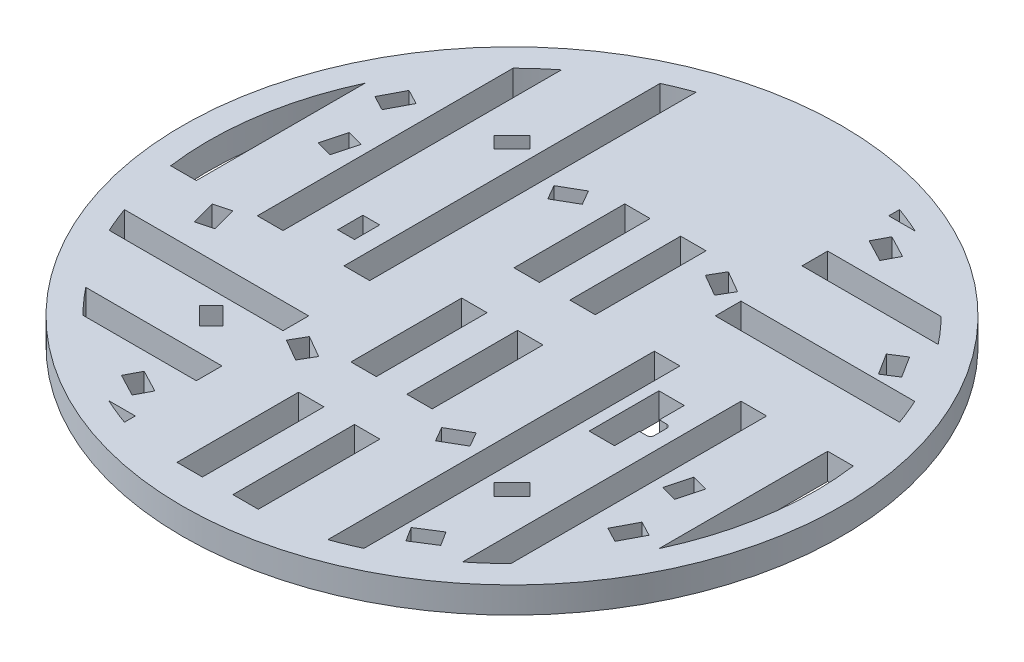
SolidWorks part; units mm, degrees
material "Acrylic (Medium-high impact)"
ref_plane "Front Plane" through (0, 0, 0) normal (0, 0, 1) x (1, 0, 0)
ref_plane "Top Plane" through (0, 0, 0) normal (0, 1, 0) x (1, 0, 0)
ref_plane "Right Plane" through (0, 0, 0) normal (1, 0, 0) x (0, 0, -1)
sketch "스케치1" plane through (0, 0, 0) normal (0, 1, 0) x (1, 0, 0)
  line L0 (-4.66, 33.75) -> (-4.66, -33.75) construction
  line L1 (-17, -33.75) -> (17, -33.75) construction
  line L2 (-17, -33.75) -> (-17, 33.75)
  line L3 (-17, 33.75) -> (17, 33.75) construction
  line L4 (17, -33.75) -> (17, 33.75)
  line L5 (-17, -33.75) -> (17, 33.75) construction
  line L6 (-17, 33.75) -> (17, -33.75) construction
  line L7 (-4.66, 4.89) -> (-1.75, 4.89)
  line L8 (-4.66, 4.89) -> (-4.66, 17.59)
  line L9 (-4.66, 17.59) -> (-1.75, 17.59)
  line L10 (-1.75, 4.89) -> (-1.75, 17.59)
  line L11 (-4.66, 4.89) -> (-1.75, 17.59) construction
  line L12 (-4.66, 17.59) -> (-1.75, 4.89) construction
  line L13 (-4.66, -13.81) -> (-1.75, -13.81)
  line L14 (-4.66, -13.81) -> (-4.66, -1.11)
  line L15 (-4.66, -1.11) -> (-1.75, -1.11)
  line L16 (-1.75, -13.81) -> (-1.75, -1.11)
  line L17 (-4.66, -13.81) -> (-1.75, -1.11) construction
  line L18 (-4.66, -1.11) -> (-1.75, -13.81) construction
  line L19 (-4.66, 23.59) -> (-1.75, 23.59) construction
  line L20 (-4.66, 23.59) -> (-4.66, 33.75) construction
  line L21 (-4.66, 33.75) -> (-1.75, 33.75) construction
  line L22 (-1.75, 23.59) -> (-1.75, 33.75) construction
  line L23 (-4.66, 23.59) -> (-1.75, 33.75) construction
  line L24 (-4.66, 33.75) -> (-1.75, 23.59) construction
  line L25 (-4.66, -33.75) -> (-1.75, -33.75) construction
  line L26 (-4.66, -33.75) -> (-4.66, -19.81)
  line L27 (-4.66, -19.81) -> (-1.75, -19.81)
  line L28 (-1.75, -33.75) -> (-1.75, -19.81)
  line L29 (-4.66, -33.75) -> (-1.75, -19.81) construction
  line L30 (-4.66, -19.81) -> (-1.75, -33.75) construction
  line L31 (0, 0) -> (0, 33.75) construction
  line L32 (4.66, 17.59) -> (1.75, 17.59)
  line L33 (1.75, 4.89) -> (1.75, 17.59)
  line L34 (4.66, 4.89) -> (1.75, 4.89)
  line L35 (4.66, 4.89) -> (4.66, 17.59)
  line L36 (4.66, 33.75) -> (1.75, 33.75) construction
  line L37 (1.75, 23.59) -> (1.75, 33.75) construction
  line L38 (4.66, 23.59) -> (1.75, 23.59) construction
  line L39 (4.66, 23.59) -> (4.66, 33.75) construction
  line L40 (4.66, -1.11) -> (1.75, -1.11)
  line L41 (1.75, -13.81) -> (1.75, -1.11)
  line L42 (4.66, -13.81) -> (1.75, -13.81)
  line L43 (4.66, -13.81) -> (4.66, -1.11)
  line L44 (4.66, -19.81) -> (1.75, -19.81)
  line L45 (1.75, -33.75) -> (1.75, -19.81)
  line L46 (4.66, -33.75) -> (1.75, -33.75) construction
  line L47 (4.66, -33.75) -> (4.66, -19.81)
  line L48 (-17, 33.75) -> (-4.66, 33.75)
  line L49 (-1.75, 33.75) -> (1.75, 33.75)
  line L50 (4.66, 33.75) -> (17, 33.75)
  line L51 (4.66, -33.75) -> (17, -33.75)
  line L52 (1.75, -33.75) -> (-1.75, -33.75)
  line L53 (-4.66, -33.75) -> (-17, -33.75)
  line L54 (1.75, 33.75) -> (4.66, 33.75)
  line L55 (-1.75, 33.75) -> (-4.66, 33.75)
  line L57 (-10, 24.25) -> (5, 24.25) construction
  line L58 (-10, 24.25) -> (-10, 32.25) construction
  line L59 (-10, 32.25) -> (5, 32.25) construction
  line L60 (5, 24.25) -> (5, 32.25) construction
  line L61 (-10, 24.25) -> (5, 32.25) construction
  line L62 (-10, 32.25) -> (5, 24.25) construction
  point P0 (0, 0)
  point P5 (-3.205, 11.24)
  point P11 (-3.205, -7.46)
  point P16 (-3.205, 28.67)
  point P21 (-3.205, -26.78)
  point P26 (-2.5, 28.25)
  point P27 (-3.205, -1.11)
  point P28 (-3.205, -13.81)
  dimension "D1" = 67.5
  dimension "D2" = 34
  dimension "D3" = 10.16
  dimension "D4" = 6
  dimension "D5" = 12.7
  dimension "D6" = 12.7
  dimension "D7" = 6
  dimension "D8" = 6
  dimension "D9" = 1.75
  dimension "D10" = 2.91
  dimension "D11" = 7
  dimension "D12" = 12
  dimension "D13" = 1.5
  dimension "D14" = 8
extrude "보스-돌출1" add sketch "스케치1" along normal blind 3 contours L53 L26 L27 L28 L52 L45 L44 L47 L51 L4 L50 L39 L38 L37 L49 L22 L19 L20 L48 L2 L43 L42 L41 L40 L35 L34 L33 L32 L16 L13 L14 L15 L10 L7 L8 L9
sketch "스케치2" plane through (0, 3, 0) normal (0, 1, 0) x (1, 0, 0)
  line L0 (17, 33.75) -> (-17, 33.75)
  line L1 (-4.66, -33.75) -> (-1.75, -33.75)
  line L2 (1.75, -33.75) -> (4.66, -33.75)
  line L20 (-17, -33.75) -> (-4.66, -33.75)
  line L21 (-4.66, -33.75) -> (-4.66, -19.81)
  line L22 (-4.66, -19.81) -> (-1.75, -19.81)
  line L23 (-1.75, -19.81) -> (-1.75, -33.75)
  line L24 (-1.75, -33.75) -> (1.75, -33.75)
  line L25 (1.75, -33.75) -> (1.75, -19.81)
  line L26 (1.75, -19.81) -> (4.66, -19.81)
  line L27 (4.66, -19.81) -> (4.66, -33.75)
  line L28 (4.66, -33.75) -> (17, -33.75)
  line L29 (17, -33.75) -> (17, 33.75)
  line L30 (17, 33.75) -> (-17, 33.75)
  line L39 (-17, 33.75) -> (-17, -33.75)
  line L40 (-17, -33.75) -> (-4.66, -33.75)
  line L44 (-1.75, -33.75) -> (1.75, -33.75)
  line L48 (4.66, -33.75) -> (17, -33.75)
  line L49 (17, -33.75) -> (17, 33.75)
  line L59 (-17, 33.75) -> (-17, -33.75)
  circle A0 centre (0, 0) radius 37.7897
  line M22 (-17, -33.75) -> (-4.66, -33.75)
  line M26 (-1.75, -33.75) -> (1.75, -33.75)
  line M30 (4.66, -33.75) -> (17, -33.75)
  line M31 (17, -33.75) -> (17, 33.75)
  line M32 (17, 33.75) -> (-17, 33.75)
  line M36 (17, 33.75) -> (-17, 33.75)
  line M40 (17, 33.75) -> (-17, 33.75)
  line M41 (-17, 33.75) -> (-17, -33.75)
  dimension "D1" = 0
extrude "보스-돌출2" add sketch "스케치2" against normal up to surface (3 mm away) contours A0 M41 | A0 L2 L1 M22 M30 M26 | A0 M31 | A0 L0 M32 M40 M36 up to face at (-3.205, 0, -11.24)
sketch "스케치5" plane through (0, 3, 0) normal (0, 1, 0) x (1, 0, 0)
  line L0 (-34.4762, -4.66) -> (32.6943, -4.66) construction
  line L1 (-34.4762, -4.66) -> (-31.5375, -4.66)
  line L2 (-31.5375, -4.66) -> (-31.5375, 14.6871)
  line L3 (-24.5375, 24.6625) -> (-24.5375, -4.66)
  line L4 (-24.5375, -4.66) -> (-21.5987, -4.66)
  line L5 (-21.5987, -4.66) -> (-21.5987, 27.273)
  line L6 (-14.5987, 31.5785) -> (-14.5987, -4.66)
  line L7 (-14.5987, -4.66) -> (-11.66, -4.66)
  line L8 (-11.66, -4.66) -> (-11.66, 32.7776)
  line L9 (-31.5375, -4.66) -> (-24.5375, -4.66) construction
  line L10 (-14.5987, -4.66) -> (-21.5987, -4.66) construction
  line L11 (-4.66, 4.89) -> (-4.66, -4.66) construction
  line L12 (-4.66, -4.66) -> (-11.66, -4.66) construction
  line L13 (-34.7897, 0) -> (-37.7897, 0) construction
  line L14 (31.5785, 14.5987) -> (11.66, 14.5987)
  line L16 (11.66, 11.66) -> (32.7776, 11.66)
  line L17 (24.6625, 24.5375) -> (11.66, 24.5375)
  line L19 (11.66, 21.5987) -> (27.273, 21.5987)
  line L20 (11.66, 31.5375) -> (14.6871, 31.5375)
  line L22 (14.5987, -31.5785) -> (14.5987, 4.66)
  line L23 (14.5987, 4.66) -> (11.66, 4.66)
  line L24 (11.66, 4.66) -> (11.66, -32.7776)
  line L25 (24.5375, -24.6625) -> (24.5375, 4.66)
  line L26 (24.5375, 4.66) -> (21.5987, 4.66)
  line L27 (21.5987, 4.66) -> (21.5987, -27.273)
  line L28 (31.5375, 4.66) -> (31.5375, -14.6871)
  line L29 (34.4762, 4.66) -> (31.5375, 4.66)
  line L30 (-31.5785, -14.5987) -> (-11.66, -14.5987)
  line L32 (-11.66, -11.66) -> (-32.7776, -11.66)
  line L33 (-24.6625, -24.5375) -> (-11.66, -24.5375)
  line L35 (-11.66, -21.5987) -> (-27.273, -21.5987)
  line L36 (-11.66, -31.5375) -> (-14.6871, -31.5375)
  line L38 (-4.66, -13.81) -> (-4.66, -1.11) construction
  line L39 (-11.66, -11.66) -> (-11.66, -14.5987)
  line L40 (11.66, 11.66) -> (11.66, 14.5987)
  line L41 (11.66, 31.5375) -> (11.66, 32.7776)
  line L42 (-4.66, 34.4762) -> (-4.66, 31.5375) [skipped]
  line L43 (-4.66, 24.5375) -> (-4.66, 21.5987) [skipped]
  line L44 (11.66, 21.5987) -> (11.66, 24.5375)
  line L45 (-4.66, 14.5987) -> (-4.66, 11.66) [skipped]
  line L46 (4.66, -14.5987) -> (4.66, -11.66) [skipped]
  line L47 (-11.66, -21.5987) -> (-11.66, -24.5375)
  line L48 (-11.66, -31.5375) -> (-11.66, -32.7776)
  line L49 (4.66, -34.4762) -> (4.66, -31.5375) [skipped]
  line L50 (4.66, -24.5375) -> (4.66, -21.5987) [skipped]
  arc A0 (-31.5375, 14.6871) -> (-34.7897, 0) centre (0, 0) ccw construction
  circle A1 centre (0, 0) radius 37.7897 construction
  arc A2 (-21.5987, 27.273) -> (-24.5375, 24.6625) centre (0, 0) ccw
  arc A3 (-11.66, 32.7776) -> (-14.5987, 31.5785) centre (0, 0) ccw
  arc A4 (-34.4762, -4.66) -> (-31.5375, 14.6871) centre (0, 0) cw
  circle A5 centre (0, 0) radius 37.7897 construction
  arc A6 (32.7776, 11.66) -> (31.5785, 14.5987) centre (0, 0) ccw
  arc A7 (27.273, 21.5987) -> (24.6625, 24.5375) centre (0, 0) ccw
  arc A8 (11.66, 32.7776) -> (14.6871, 31.5375) centre (0, 0) cw
  arc A9 (11.66, -32.7776) -> (14.5987, -31.5785) centre (0, 0) ccw
  arc A10 (21.5987, -27.273) -> (24.5375, -24.6625) centre (0, 0) ccw
  arc A11 (34.4762, 4.66) -> (31.5375, -14.6871) centre (0, 0) cw
  arc A12 (-32.7776, -11.66) -> (-31.5785, -14.5987) centre (0, 0) ccw
  arc A13 (-27.273, -21.5987) -> (-24.6625, -24.5375) centre (0, 0) ccw
  arc A14 (-11.66, -32.7776) -> (-14.6871, -31.5375) centre (0, 0) cw
  point P59 (0, 0)
  dimension "D1" = 3
  dimension "D3" = 4
  dimension "D2" = 7
  dimension "D4" = 7
extrude "컷-돌출3" cut sketch "스케치5" against normal up to surface (3 mm away)
sketch "스케치3" plane through (0, 3, 0) normal (0, 1, 0) x (1, 0, 0)
  line L0 (0, 0) -> (-17.5618, -33.4611) construction
  line L1 (-13.9217, -29.6404) -> (-16.4851, -28.295)
  line L2 (-13.9217, -29.6404) -> (-13.0248, -27.9315)
  line L3 (-16.4851, -28.295) -> (-15.5882, -26.5861)
  line L4 (-13.0248, -27.9315) -> (-15.5882, -26.5861)
  line L5 (-13.9217, -29.6404) -> (-15.5882, -26.5861) construction
  line L6 (-16.4851, -28.295) -> (-13.0248, -27.9315) construction
  line L7 (0, 0) -> (0, -37.7897) construction
  line L8 (-26.8768, -18.7085) -> (-28.424, -16.2616) construction
  line L9 (-26.8768, -18.7085) -> (-25.2455, -17.6769) construction
  line L10 (-25.2455, -17.6769) -> (-26.7928, -15.2301) construction
  line L11 (-28.424, -16.2616) -> (-26.7928, -15.2301) construction
  line L12 (-32.6302, -2.7636) -> (-32.7468, 0.129) construction
  line L13 (-32.6302, -2.7636) -> (-30.7017, -2.6859) construction
  line L14 (-30.7017, -2.6859) -> (-30.8183, 0.2067) construction
  line L15 (-32.7468, 0.129) -> (-30.8183, 0.2067) construction
  line L16 (-29.6404, 13.9217) -> (-28.295, 16.4851)
  line L17 (-29.6404, 13.9217) -> (-27.9315, 13.0248)
  line L18 (-27.9315, 13.0248) -> (-26.5861, 15.5882)
  line L19 (-28.295, 16.4851) -> (-26.5861, 15.5882)
  line L20 (-18.7085, 26.8768) -> (-16.2616, 28.424) construction
  line L21 (-18.7085, 26.8768) -> (-17.6769, 25.2455) construction
  line L22 (-17.6769, 25.2455) -> (-15.2301, 26.7928) construction
  line L23 (-16.2616, 28.424) -> (-15.2301, 26.7928) construction
  line L24 (-2.7636, 32.6302) -> (0.129, 32.7468) construction
  line L25 (-2.7636, 32.6302) -> (-2.6859, 30.7017) construction
  line L26 (-2.6859, 30.7017) -> (0.2067, 30.8183) construction
  line L27 (0.129, 32.7468) -> (0.2067, 30.8183) construction
  line L28 (13.9217, 29.6404) -> (16.4851, 28.295)
  line L29 (13.9217, 29.6404) -> (13.0248, 27.9315)
  line L30 (13.0248, 27.9315) -> (15.5882, 26.5861)
  line L31 (16.4851, 28.295) -> (15.5882, 26.5861)
  line L32 (26.8768, 18.7085) -> (28.424, 16.2616)
  line L33 (26.8768, 18.7085) -> (25.2455, 17.6769)
  line L34 (25.2455, 17.6769) -> (26.7928, 15.2301)
  line L35 (28.424, 16.2616) -> (26.7928, 15.2301)
  line L36 (32.6302, 2.7636) -> (32.7468, -0.129) construction
  line L37 (32.6302, 2.7636) -> (30.7017, 2.6859) construction
  line L38 (30.7017, 2.6859) -> (30.8183, -0.2067) construction
  line L39 (32.7468, -0.129) -> (30.8183, -0.2067) construction
  line L40 (29.6404, -13.9217) -> (28.295, -16.4851)
  line L41 (29.6404, -13.9217) -> (27.9315, -13.0248)
  line L42 (27.9315, -13.0248) -> (26.5861, -15.5882)
  line L43 (28.295, -16.4851) -> (26.5861, -15.5882)
  line L44 (0, 0) -> (-9.7807, -36.5021) construction
  line L45 (-8.8793, -27.5454) -> (-6.083, -28.2947) construction
  line L46 (-8.8793, -27.5454) -> (-8.3798, -25.6812) construction
  line L47 (-6.083, -28.2947) -> (-5.5835, -26.4305) construction
  line L48 (-8.3798, -25.6812) -> (-5.5835, -26.4305) construction
  line L49 (-8.8793, -27.5454) -> (-5.5835, -26.4305) construction
  line L50 (-6.083, -28.2947) -> (-8.3798, -25.6812) construction
  line L51 (-21.4625, -19.4154) -> (-19.4154, -21.4625) construction
  line L52 (-21.4625, -19.4154) -> (-20.0977, -18.0507) construction
  line L53 (-20.0977, -18.0507) -> (-18.0507, -20.0977) construction
  line L54 (-19.4154, -21.4625) -> (-18.0507, -20.0977) construction
  line L55 (-28.2947, -6.083) -> (-27.5454, -8.8793)
  line L56 (-28.2947, -6.083) -> (-26.4305, -5.5835)
  line L57 (-26.4305, -5.5835) -> (-25.6812, -8.3798)
  line L58 (-27.5454, -8.8793) -> (-25.6812, -8.3798)
  line L59 (-27.5454, 8.8793) -> (-28.2947, 6.083)
  line L60 (-27.5454, 8.8793) -> (-25.6812, 8.3798)
  line L61 (-25.6812, 8.3798) -> (-26.4305, 5.5835)
  line L62 (-28.2947, 6.083) -> (-26.4305, 5.5835)
  line L63 (-19.4154, 21.4625) -> (-21.4625, 19.4154) construction
  line L64 (-19.4154, 21.4625) -> (-18.0507, 20.0977) construction
  line L65 (-18.0507, 20.0977) -> (-20.0977, 18.0507) construction
  line L66 (-21.4625, 19.4154) -> (-20.0977, 18.0507) construction
  line L67 (-6.083, 28.2947) -> (-8.8793, 27.5454) construction
  line L68 (-6.083, 28.2947) -> (-5.5835, 26.4305) construction
  line L69 (-5.5835, 26.4305) -> (-8.3798, 25.6812) construction
  line L70 (-8.8793, 27.5454) -> (-8.3798, 25.6812) construction
  line L71 (8.8793, 27.5454) -> (6.083, 28.2947) construction
  line L72 (8.8793, 27.5454) -> (8.3798, 25.6812) construction
  line L73 (8.3798, 25.6812) -> (5.5835, 26.4305) construction
  line L74 (6.083, 28.2947) -> (5.5835, 26.4305) construction
  line L75 (21.4625, 19.4154) -> (19.4154, 21.4625) construction
  line L76 (21.4625, 19.4154) -> (20.0977, 18.0507) construction
  line L77 (20.0977, 18.0507) -> (18.0507, 20.0977) construction
  line L78 (19.4154, 21.4625) -> (18.0507, 20.0977) construction
  line L79 (28.2947, 6.083) -> (27.5454, 8.8793) construction
  line L80 (28.2947, 6.083) -> (26.4305, 5.5835) construction
  line L81 (26.4305, 5.5835) -> (25.6812, 8.3798) construction
  line L82 (27.5454, 8.8793) -> (25.6812, 8.3798) construction
  line L83 (27.5454, -8.8793) -> (28.2947, -6.083)
  line L84 (27.5454, -8.8793) -> (25.6812, -8.3798)
  line L85 (25.6812, -8.3798) -> (26.4305, -5.5835)
  line L86 (28.2947, -6.083) -> (26.4305, -5.5835)
  line L87 (-18.948, -16.9009) -> (-16.9009, -18.948)
  line L88 (-18.948, -16.9009) -> (-17.5833, -15.5362)
  line L89 (-16.9009, -18.948) -> (-15.5362, -17.5833)
  line L90 (-17.5833, -15.5362) -> (-15.5362, -17.5833)
  line L91 (-18.948, -16.9009) -> (-15.5362, -17.5833) construction
  line L92 (-16.9009, -18.948) -> (-17.5833, -15.5362) construction
  line L93 (-23.9734, -8.3633) -> (-22.8655, -11.038) construction
  line L94 (-23.9734, -8.3633) -> (-22.1903, -7.6247) construction
  line L95 (-22.1903, -7.6247) -> (-21.0824, -10.2994) construction
  line L96 (-22.8655, -11.038) -> (-21.0824, -10.2994) construction
  line L97 (-25.349, 1.4475) -> (-25.349, -1.4475) construction
  line L98 (-25.349, 1.4475) -> (-23.419, 1.4475) construction
  line L99 (-23.419, 1.4475) -> (-23.419, -1.4475) construction
  line L100 (-25.349, -1.4475) -> (-23.419, -1.4475) construction
  line L101 (-22.8655, 11.038) -> (-23.9734, 8.3633) construction
  line L102 (-22.8655, 11.038) -> (-21.0824, 10.2994) construction
  line L103 (-21.0824, 10.2994) -> (-22.1903, 7.6247) construction
  line L104 (-23.9734, 8.3633) -> (-22.1903, 7.6247) construction
  line L105 (-16.9009, 18.948) -> (-18.948, 16.9009)
  line L106 (-16.9009, 18.948) -> (-15.5362, 17.5833)
  line L107 (-15.5362, 17.5833) -> (-17.5833, 15.5362)
  line L108 (-18.948, 16.9009) -> (-17.5833, 15.5362)
  line L129 (0, 0) -> (-26.7214, -26.7214) construction
  line L131 (25.5959, -3.5352) -> (22.7009, -3.5352) construction
  line L132 (25.5959, -3.5352) -> (25.5959, 4.4648) construction
  line L133 (25.5959, 4.4648) -> (22.7009, 4.4648) construction
  line L134 (22.7009, -3.5352) -> (22.7009, 4.4648) construction
  line L135 (25.5959, -3.5352) -> (22.7009, 4.4648) construction
  line L136 (25.5959, 4.4648) -> (22.7009, -3.5352) construction
  line L138 (25.675, -7.0176) -> (28.57, -7.0176) construction
  line L139 (25.675, -7.0176) -> (25.675, 0.9824) construction
  line L140 (25.675, 0.9824) -> (28.57, 0.9824) construction
  line L141 (28.57, -7.0176) -> (28.57, 0.9824) construction
  line L142 (25.675, -7.0176) -> (28.57, 0.9824) construction
  line L143 (25.675, 0.9824) -> (28.57, -7.0176) construction
  line L145 (15.862, -7.0176) -> (18.772, -7.0176)
  line L146 (15.862, -7.0176) -> (15.862, 0.9824)
  line L147 (15.862, 0.9824) -> (18.772, 0.9824)
  line L148 (18.772, -7.0176) -> (18.772, 0.9824) construction
  line L149 (15.862, -7.0176) -> (18.772, 0.9824) construction
  line L150 (15.862, 0.9824) -> (18.772, -7.0176) construction
  line L151 (17.317, -3.0176) -> (27.1225, -3.0176) construction
  line L152 (18.7085, -26.8768) -> (16.2616, -28.424)
  line L153 (18.7085, -26.8768) -> (17.6769, -25.2455)
  line L154 (17.6769, -25.2455) -> (15.2301, -26.7928)
  line L155 (16.2616, -28.424) -> (15.2301, -26.7928)
  line L156 (2.7636, -32.6302) -> (-0.129, -32.7468) construction
  line L157 (2.7636, -32.6302) -> (2.6859, -30.7017) construction
  line L158 (2.6859, -30.7017) -> (-0.2067, -30.8183) construction
  line L159 (-0.129, -32.7468) -> (-0.2067, -30.8183) construction
  line L160 (19.4154, -21.4625) -> (21.4625, -19.4154) construction
  line L161 (19.4154, -21.4625) -> (18.0507, -20.0977) construction
  line L162 (18.0507, -20.0977) -> (20.0977, -18.0507) construction
  line L163 (21.4625, -19.4154) -> (20.0977, -18.0507) construction
  line L164 (6.083, -28.2947) -> (8.8793, -27.5454) construction
  line L165 (6.083, -28.2947) -> (5.5835, -26.4305) construction
  line L166 (5.5835, -26.4305) -> (8.3798, -25.6812) construction
  line L167 (8.8793, -27.5454) -> (8.3798, -25.6812) construction
  line L168 (-8.3633, 23.9734) -> (-11.038, 22.8655) construction
  line L169 (-8.3633, 23.9734) -> (-7.6247, 22.1903) construction
  line L170 (-7.6247, 22.1903) -> (-10.2994, 21.0824) construction
  line L171 (-11.038, 22.8655) -> (-10.2994, 21.0824) construction
  line L172 (1.4475, 25.349) -> (-1.4475, 25.349) construction
  line L173 (1.4475, 25.349) -> (1.4475, 23.419) construction
  line L174 (1.4475, 23.419) -> (-1.4475, 23.419) construction
  line L175 (-1.4475, 25.349) -> (-1.4475, 23.419) construction
  line L176 (11.038, 22.8655) -> (8.3633, 23.9734) construction
  line L177 (11.038, 22.8655) -> (10.2994, 21.0824) construction
  line L178 (10.2994, 21.0824) -> (7.6247, 22.1903) construction
  line L179 (8.3633, 23.9734) -> (7.6247, 22.1903) construction
  line L180 (18.948, 16.9009) -> (16.9009, 18.948) construction
  line L181 (18.948, 16.9009) -> (17.5833, 15.5362) construction
  line L182 (17.5833, 15.5362) -> (15.5362, 17.5833) construction
  line L183 (16.9009, 18.948) -> (15.5362, 17.5833) construction
  line L184 (23.9734, 8.3633) -> (22.8655, 11.038) construction
  line L185 (23.9734, 8.3633) -> (22.1903, 7.6247) construction
  line L186 (22.1903, 7.6247) -> (21.0824, 10.2994) construction
  line L187 (22.8655, 11.038) -> (21.0824, 10.2994) construction
  line L188 (25.349, -1.4475) -> (25.349, 1.4475) construction
  line L189 (25.349, -1.4475) -> (23.419, -1.4475) construction
  line L190 (23.419, -1.4475) -> (23.419, 1.4475) construction
  line L191 (25.349, 1.4475) -> (23.419, 1.4475) construction
  line L192 (22.8655, -11.038) -> (23.9734, -8.3633) construction
  line L193 (22.8655, -11.038) -> (21.0824, -10.2994) construction
  line L194 (21.0824, -10.2994) -> (22.1903, -7.6247) construction
  line L195 (23.9734, -8.3633) -> (22.1903, -7.6247) construction
  line L196 (16.9009, -18.948) -> (18.948, -16.9009)
  line L197 (16.9009, -18.948) -> (15.5362, -17.5833)
  line L198 (15.5362, -17.5833) -> (17.5833, -15.5362)
  line L199 (18.948, -16.9009) -> (17.5833, -15.5362)
  line L200 (8.3633, -23.9734) -> (11.038, -22.8655) construction
  line L201 (8.3633, -23.9734) -> (7.6247, -22.1903) construction
  line L202 (7.6247, -22.1903) -> (10.2994, -21.0824) construction
  line L203 (11.038, -22.8655) -> (10.2994, -21.0824) construction
  line L204 (-1.4475, -25.349) -> (1.4475, -25.349) construction
  line L205 (-1.4475, -25.349) -> (-1.4475, -23.419) construction
  line L206 (-1.4475, -23.419) -> (1.4475, -23.419) construction
  line L207 (1.4475, -25.349) -> (1.4475, -23.419) construction
  line L208 (-11.038, -22.8655) -> (-8.3633, -23.9734) construction
  line L209 (-11.038, -22.8655) -> (-10.2994, -21.0824) construction
  line L210 (-10.2994, -21.0824) -> (-7.6247, -22.1903) construction
  line L211 (-8.3633, -23.9734) -> (-7.6247, -22.1903) construction
  line L212 (0, 0) -> (-17.5833, 0) construction
  line L213 (-10.5277, 15.3395) -> (-8.0206, 16.787)
  line L214 (-18.5483, -1.4475) -> (-16.6183, -1.4475)
  line L215 (-18.5483, -1.4475) -> (-18.5483, 1.4475)
  line L216 (-18.5483, 1.4475) -> (-16.6183, 1.4475)
  line L217 (-16.6183, -1.4475) -> (-16.6183, 1.4475)
  line L218 (-18.5483, -1.4475) -> (-16.6183, 1.4475) construction
  line L219 (-18.5483, 1.4475) -> (-16.6183, -1.4475) construction
  line L220 (-10.5277, 15.3395) -> (-9.5627, 13.6681)
  line L221 (-9.5627, 13.6681) -> (-7.0556, 15.1156)
  line L222 (-8.0206, 16.787) -> (-7.0556, 15.1156)
  line L223 (8.0206, 16.787) -> (10.5277, 15.3395)
  line L224 (8.0206, 16.787) -> (7.0556, 15.1156)
  line L225 (7.0556, 15.1156) -> (9.5627, 13.6681)
  line L226 (10.5277, 15.3395) -> (9.5627, 13.6681)
  line L227 (18.5483, 1.4475) -> (18.5483, -1.4475) construction
  line L228 (18.5483, 1.4475) -> (16.6183, 1.4475) construction
  line L229 (16.6183, 1.4475) -> (16.6183, -1.4475) construction
  line L230 (18.5483, -1.4475) -> (16.6183, -1.4475) construction
  line L231 (10.5277, -15.3395) -> (8.0206, -16.787)
  line L232 (10.5277, -15.3395) -> (9.5627, -13.6681)
  line L233 (9.5627, -13.6681) -> (7.0556, -15.1156)
  line L234 (8.0206, -16.787) -> (7.0556, -15.1156)
  line L235 (-8.0206, -16.787) -> (-10.5277, -15.3395)
  line L236 (-8.0206, -16.787) -> (-7.0556, -15.1156)
  line L237 (-7.0556, -15.1156) -> (-9.5627, -13.6681)
  line L238 (-10.5277, -15.3395) -> (-9.5627, -13.6681)
  line L239 (18.772, -1.8746) -> (18.772, 0.9824)
  line L240 (18.772, -4.1606) -> (19.614, -4.1606)
  line L241 (18.772, -4.1606) -> (18.772, -1.8746) construction
  line L242 (18.772, -1.8746) -> (19.614, -1.8746)
  line L243 (20.042, -3.7326) -> (20.042, -2.3026)
  line L244 (18.772, -4.1606) -> (20.042, -1.8746) construction
  line L245 (18.772, -1.8746) -> (20.042, -4.1606) construction
  line L246 (18.772, -4.1606) -> (18.772, -7.0176)
  circle A0 centre (0, 0) radius 37.7897 construction
  arc A1 (19.614, -4.1606) -> (20.042, -3.7326) centre (19.614, -3.7326) ccw
  arc A2 (19.614, -1.8746) -> (20.042, -2.3026) centre (19.614, -2.3026) cw
  point P6 (-14.755, -28.1132)
  point P7 (24.1484, 0.4648)
  point P9 (-7.2314, -26.988)
  point P50 (0, 0)
  point P51 (-17.2421, -17.2421)
  point P93 (0, 0)
  point P135 (0, 0)
  point P144 (17.317, -3.0176)
  point P145 (27.1225, -3.0176)
  point P197 (19.407, -3.0176)
  point P218 (0, 0)
  dimension "D19" = 1.27
  dimension "D21" = 0.428
  dimension "D1" = 2.895
  dimension "D2" = 1.93
  dimension "D3" = 27.692
  dimension "D5" = 31.75
  dimension "D6" = 15
  dimension "D7" = 27.94
  dimension "D8" = 12
  dimension "D9" = 24.384
  dimension "D10" = 16
  dimension "D11" = 30
  dimension "D12" = 2.895
  dimension "D13" = 8
  dimension "D14" = 1.9076
  dimension "D15" = 27.1225
  dimension "D16" = 2.91
  dimension "D17" = 8
  dimension "D18" = 6
  dimension "D20" = 2.286
  dimension "D4" = 12
extrude "컷-돌출1" cut sketch "스케치3" against normal up to surface (3 mm away) up to face at (12.6739, 0, -31.9627)
